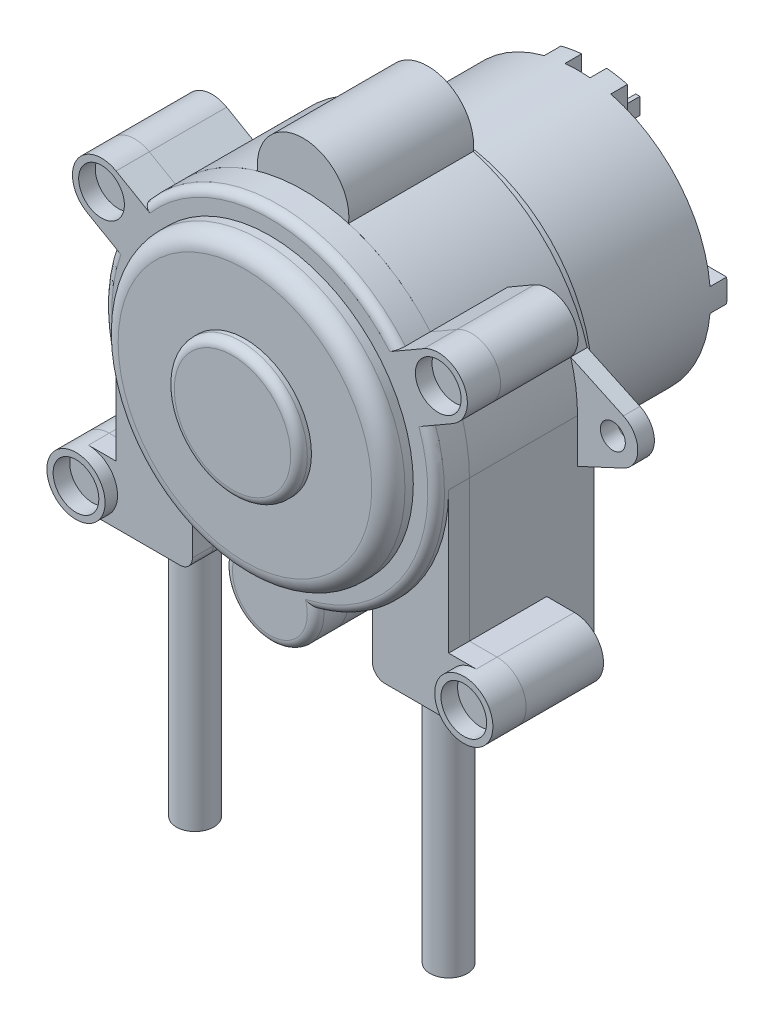
SolidWorks part; units mm, degrees
material "ABS"
ref_plane "Frontal" through (0, 0, 0) normal (0, 0, 1) x (1, 0, 0)
ref_plane "Superior" through (0, 0, 0) normal (0, 1, 0) x (1, 0, 0)
ref_plane "Direito" through (0, 0, 0) normal (1, 0, 0) x (0, 0, -1)
sketch "Esboço1" plane through (0, 0, 0) normal (0, 0, 1) x (1, 0, 0)
  line L0 (-20, 0) -> (20, 0) construction
  line L1 (-20, 0) -> (-20, -17)
  line L2 (-20, -17) -> (-23.325, -17)
  line L3 (-23.325, -24) -> (-12.325, -24)
  line L4 (-10.825, -22.5) -> (-10.825, -16.8172)
  line L5 (0, 20) -> (0, -20) construction
  line L6 (0, 0) -> (-20.25, 11.6913) construction
  line L7 (-18.5, 14.7224) -> (-15.3032, 12.8768)
  line L8 (-22, 8.6603) -> (-18.8032, 6.8146)
  line L9 (18.5, 14.7224) -> (15.3032, 12.8768)
  line L10 (22, 8.6603) -> (18.8032, 6.8146)
  line L11 (10.825, -22.5) -> (10.825, -16.8172)
  line L12 (23.325, -24) -> (12.325, -24)
  line L13 (20, -17) -> (23.325, -17)
  line L14 (20, 0) -> (20, -17)
  arc A0 (15.3032, 12.8768) -> (5.4603, 19.2402) centre (0, 0) ccw
  arc A1 (-23.325, -17) -> (-23.325, -24) centre (-23.325, -20.5) ccw
  arc A2 (-18.5, 14.7224) -> (-22, 8.6603) centre (-20.25, 11.6913) ccw
  arc A3 (18.5, 14.7224) -> (22, 8.6603) centre (20.25, 11.6913) cw
  arc A4 (-18.8032, 6.8146) -> (-20, 0) centre (0, 0) ccw
  arc A5 (-10.825, -16.8172) -> (-5.4603, -19.2402) centre (0, 0) ccw
  arc A6 (23.325, -17) -> (23.325, -24) centre (23.325, -20.5) cw
  arc A7 (20, 0) -> (18.8032, 6.8146) centre (0, 0) ccw
  arc A8 (5.4603, -19.2402) -> (-5.4603, -19.2402) centre (0, -19.9) cw
  arc A9 (5.4603, 19.2402) -> (-5.4603, 19.2402) centre (0, 19.9) ccw
  arc A10 (-5.4603, 19.2402) -> (-15.3032, 12.8768) centre (0, 0) ccw
  arc A11 (5.4603, -19.2402) -> (10.825, -16.8172) centre (0, 0) ccw
  arc A12 (10.825, -22.5) -> (12.325, -24) centre (12.325, -22.5) ccw
  arc A13 (-12.325, -24) -> (-10.825, -22.5) centre (-12.325, -22.5) ccw
  point P34 (0, -25.4)
  point P35 (0, 25.4)
  point P36 (26.825, -20.5)
  point P37 (-26.825, -20.5)
  point P40 (10.825, -24)
  point P43 (-10.825, -24)
  dimension "D1" = 40
  dimension "D4" = 47.5
  dimension "D7" = 7
  dimension "D6" = 5.5
  dimension "D8" = 53.65
  dimension "D11" = 1.5
  dimension "D2" = 60
  dimension "D3" = 7
  dimension "D5" = 50.8
  dimension "D9" = 44
  dimension "D10" = 16
extrude "Ressalto-extrusão1" add sketch "Esboço1" along normal blind 15
sketch "Esboço2" plane through (0, 0, 0) normal (0, 0, -1) x (-1, 0, 0)
  line L0 (-20, -17) -> (-20, -24)
  line L1 (20, -17) -> (20, -24)
  line L12 (-20, 0) -> (-20, -17)
  line L13 (-20, -17) -> (-23.325, -17)
  line L14 (-23.325, -24) -> (-12.325, -24)
  line L15 (-10.825, -22.5) -> (-10.825, -16.8172)
  line L16 (10.825, -16.8172) -> (10.825, -22.5)
  line L17 (12.325, -24) -> (23.325, -24)
  line L18 (23.325, -17) -> (20, -17)
  line L19 (20, -17) -> (20, 0)
  line L20 (18.8032, 6.8146) -> (22, 8.6603)
  line L21 (18.5, 14.7224) -> (15.3032, 12.8768)
  line L22 (-15.3032, 12.8768) -> (-18.5, 14.7224)
  line L23 (-22, 8.6603) -> (-18.8032, 6.8146)
  line L25 (-20, -17) -> (-23.325, -17)
  line L26 (-23.325, -24) -> (-20, -24)
  line L29 (20, -24) -> (23.325, -24)
  line L30 (23.325, -17) -> (20, -17)
  line L32 (18.8032, 6.8146) -> (22, 8.6603)
  line L33 (18.5, 14.7224) -> (15.3032, 12.8768)
  line L34 (-15.3032, 12.8768) -> (-18.5, 14.7224)
  line L35 (-22, 8.6603) -> (-18.8032, 6.8146)
  arc A1 (-15.3032, 12.8768) -> (-18.8032, 6.8146) centre (0, 0) ccw
  arc A3 (18.8032, 6.8146) -> (15.3032, 12.8768) centre (0, 0) ccw
  arc A13 (-18.8032, 6.8146) -> (-20, 0) centre (0, 0) ccw
  arc A14 (-23.325, -17) -> (-23.325, -24) centre (-23.325, -20.5) ccw
  arc A15 (-10.825, -16.8172) -> (-5.4603, -19.2402) centre (0, 0) ccw
  arc A16 (-5.4603, -19.2402) -> (5.4603, -19.2402) centre (0, -19.9) ccw
  arc A17 (5.4603, -19.2402) -> (10.825, -16.8172) centre (0, 0) ccw
  arc A18 (23.325, -24) -> (23.325, -17) centre (23.325, -20.5) ccw
  arc A19 (20, 0) -> (18.8032, 6.8146) centre (0, 0) ccw
  arc A20 (22, 8.6603) -> (18.5, 14.7224) centre (20.25, 11.6913) ccw
  arc A21 (15.3032, 12.8768) -> (5.4603, 19.2402) centre (0, 0) ccw
  arc A22 (5.4603, 19.2402) -> (-5.4603, 19.2402) centre (0, 19.9) ccw
  arc A23 (-5.4603, 19.2402) -> (-15.3032, 12.8768) centre (0, 0) ccw
  arc A24 (-18.5, 14.7224) -> (-22, 8.6603) centre (-20.25, 11.6913) ccw
  arc A26 (-23.325, -17) -> (-23.325, -24) centre (-23.325, -20.5) ccw
  arc A30 (23.325, -24) -> (23.325, -17) centre (23.325, -20.5) ccw
  arc A32 (22, 8.6603) -> (18.5, 14.7224) centre (20.25, 11.6913) ccw
  arc A36 (-18.5, 14.7224) -> (-22, 8.6603) centre (-20.25, 11.6913) ccw
  arc A42 (-12.325, -24) -> (-10.825, -22.5) centre (-12.325, -22.5) ccw
  arc A44 (10.825, -22.5) -> (12.325, -24) centre (12.325, -22.5) ccw
  dimension "D1" = 0
extrude "Corte-extrusão1" cut sketch "Esboço2" against normal blind 5.7
sketch "Esboço3" plane through (0, 0, 0) normal (0, 0, -1) x (-1, 0, 0)
  line L0 (-24.25, 0) -> (24.25, 0) construction
  line L1 (-25.5179, 2.7189) -> (0, 14.6181)
  line L2 (-25.5179, -2.7189) -> (0, -14.6181)
  line L3 (25.5179, 2.7189) -> (0, 14.6181)
  line L4 (25.5179, -2.7189) -> (0, -14.6181)
  circle A0 centre (-24.25, 0) radius 1.5
  circle A1 centre (24.25, 0) radius 1.5
  arc A2 (25.5179, 2.7189) -> (25.5179, -2.7189) centre (24.25, 0) cw
  arc A3 (-25.5179, 2.7189) -> (-25.5179, -2.7189) centre (-24.25, 0) ccw
  point P4 (0, 0)
  point P15 (27.25, 0)
  point P16 (-27.25, 0)
  dimension "D2" = 3
  dimension "D3" = 54.5
  dimension "D1" = 48.5
  dimension "D4" = 50
extrude "Ressalto-extrusão2" add sketch "Esboço3" against normal blind 2
sketch "Esboço4" plane through (0, 0, 15) normal (0, 0, 1) x (1, 0, 0)
  circle A0 centre (0, 0) radius 18
  arc A1 (15.3032, 12.8768) -> (5.4603, 19.2402) centre (0, 0) ccw construction
  dimension "D1" = 2
extrude "Corte-extrusão2" cut sketch "Esboço4" against normal blind 10
sketch "Esboço5" plane through (0, 0, 0) normal (0, 0, -1) x (-1, 0, 0)
  circle A0 centre (0, 0) radius 17.25
  dimension "D1" = 34.5
extrude "Ressalto-extrusão3" add sketch "Esboço5" along normal blind 2.5
sketch "Esboço6" plane through (0, 0, -2.5) normal (0, 0, -1) x (-1, 0, 0)
  circle A0 centre (0, 0) radius 16
  dimension "D1" = 32
extrude "Ressalto-extrusão4" add sketch "Esboço6" along normal blind 17.5 separate body
sketch "Esboço7" plane through (0, 0, -20) normal (0, 0, -1) x (-1, 0, 0)
  circle A0 centre (0, 0) radius 3.65
  dimension "D1" = 7.3
extrude "Ressalto-extrusão5" add sketch "Esboço7" along normal blind 3.5
sketch "Esboço8" plane through (0, 0, -20) normal (0, 0, -1) x (-1, 0, 0)
  line L0 (0, 16) -> (0, -16) construction
  line L1 (-16, 0) -> (16, 0) construction
  line L2 (-4, 15.4919) -> (-4, 3.4)
  line L3 (4, 15.4919) -> (4, 3.4)
  line L4 (-15.9386, -1.4) -> (-6, -1.4)
  line L5 (-15.9386, 1.4) -> (-6, 1.4)
  line L6 (-4, 16) -> (-4, -16) construction
  line L7 (4, 16) -> (4, -16) construction
  line L8 (4, -3.4) -> (4, -15.4919)
  line L9 (6, 1.4) -> (15.9386, 1.4)
  line L10 (-16, 1.4) -> (16, 1.4) construction
  line L11 (-4, -3.4) -> (-4, -15.4919)
  line L12 (6, -1.4) -> (15.9386, -1.4)
  line L13 (-16, -1.4) -> (16, -1.4) construction
  line L15 (-1.5, 19.15) -> (1.5, 19.15)
  line L16 (-1.5, 19.15) -> (-1.5, 12.85)
  line L17 (-1.5, 12.85) -> (1.5, 12.85)
  line L18 (1.5, 19.15) -> (1.5, 12.85)
  line L19 (-1.5, 19.15) -> (1.5, 12.85) construction
  line L20 (-1.5, 12.85) -> (1.5, 19.15) construction
  line L21 (-1.5, -12.85) -> (1.5, -12.85)
  line L22 (-1.5, -12.85) -> (-1.5, -19.15)
  line L23 (-1.5, -19.15) -> (1.5, -19.15)
  line L24 (1.5, -12.85) -> (1.5, -19.15)
  line L25 (-1.5, -12.85) -> (1.5, -19.15) construction
  line L26 (-1.5, -19.15) -> (1.5, -12.85) construction
  circle A0 centre (0, 0) radius 16 construction
  arc A1 (-4, 15.4919) -> (-15.9386, 1.4) centre (0, 0) ccw
  arc A2 (15.9386, 1.4) -> (4, 15.4919) centre (0, 0) ccw
  arc A3 (4, -15.4919) -> (15.9386, -1.4) centre (0, 0) ccw
  arc A4 (-15.9386, -1.4) -> (-4, -15.4919) centre (0, 0) ccw
  arc A5 (4, 3.4) -> (6, 1.4) centre (6, 3.4) ccw
  arc A6 (6, -1.4) -> (4, -3.4) centre (6, -3.4) ccw
  arc A7 (-4, -3.4) -> (-6, -1.4) centre (-6, -3.4) ccw
  arc A8 (-6, 1.4) -> (-4, 3.4) centre (-6, 3.4) ccw
  point P29 (4, 1.4)
  dimension "D5" = 2
  dimension "D6" = 3
  dimension "D7" = 25.7
  dimension "D1" = 4
  dimension "D2" = 4
  dimension "D3" = 1.4
  dimension "D4" = 1.4
extrude "Corte-extrusão3" cut sketch "Esboço8" against normal blind 2
sketch "Esboço9" plane through (0, 0, -20) normal (0, 0, -1) x (-1, 0, 0)
  line L0 (-4, 3.4) -> (-4, 15.4919) construction
  line L1 (-2, 11.5) -> (-1.5, 11.5)
  line L2 (-2, 11.5) -> (-2, 9.5)
  line L3 (-2, 9.5) -> (-1.5, 9.5)
  line L4 (-1.5, 11.5) -> (-1.5, 9.5)
  line L5 (-2, 11.5) -> (-1.5, 9.5) construction
  line L6 (-2, 9.5) -> (-1.5, 11.5) construction
  line L7 (1.5, -11.5) -> (2, -11.5)
  line L8 (1.5, -11.5) -> (1.5, -9.5)
  line L9 (1.5, -9.5) -> (2, -9.5)
  line L10 (2, -11.5) -> (2, -9.5)
  line L11 (1.5, -11.5) -> (2, -9.5) construction
  line L12 (1.5, -9.5) -> (2, -11.5) construction
  line L13 (4, -3.4) -> (4, -15.4919) construction
  point P0 (-1.75, 10.5)
  point P5 (1.75, -10.5)
  dimension "D1" = 2
  dimension "D2" = 0.5
  dimension "D3" = 2.5
  dimension "D4" = 11.5
  dimension "D5" = 11.5
  dimension "D6" = 2.5
extrude "Ressalto-extrusão6" add sketch "Esboço9" along normal blind 3.5
sketch "Esboço10" plane through (0, 0, 15) normal (0, 0, 1) x (1, 0, 0)
  line L12 (18.8032, 6.8146) -> (22, 8.6603)
  line L13 (18.5, 14.7224) -> (15.3032, 12.8768)
  line L14 (-15.3032, 12.8768) -> (-18.5, 14.7224)
  line L15 (-22, 8.6603) -> (-18.8032, 6.8146)
  line L16 (-20, 0) -> (-20, -17)
  line L17 (-20, -17) -> (-23.325, -17)
  line L18 (-23.325, -24) -> (-12.325, -24)
  line L19 (-10.825, -22.5) -> (-10.825, -16.8172)
  line L20 (10.825, -16.8172) -> (10.825, -22.5)
  line L21 (12.325, -24) -> (23.325, -24)
  line L22 (23.325, -17) -> (20, -17)
  line L23 (20, -17) -> (20, 0)
  line L24 (18.8032, 6.8146) -> (22, 8.6603)
  line L25 (18.5, 14.7224) -> (15.3032, 12.8768)
  line L26 (-15.3032, 12.8768) -> (-18.5, 14.7224)
  line L27 (-22, 8.6603) -> (-18.8032, 6.8146)
  line L28 (-20, 0) -> (-20, -17)
  line L29 (-20, -17) -> (-23.325, -17)
  line L30 (-23.325, -24) -> (-12.325, -24)
  line L31 (-10.825, -22.5) -> (-10.825, -16.8172)
  line L32 (10.825, -16.8172) -> (10.825, -22.5)
  line L33 (12.325, -24) -> (23.325, -24)
  line L34 (23.325, -17) -> (20, -17)
  line L35 (20, -17) -> (20, 0)
  arc A12 (20, 0) -> (18.8032, 6.8146) centre (0, 0) ccw
  arc A13 (22, 8.6603) -> (18.5, 14.7224) centre (20.25, 11.6913) ccw
  arc A14 (15.3032, 12.8768) -> (5.4603, 19.2402) centre (0, 0) ccw
  arc A15 (5.4603, 19.2402) -> (-5.4603, 19.2402) centre (0, 19.9) ccw
  arc A16 (-5.4603, 19.2402) -> (-15.3032, 12.8768) centre (0, 0) ccw
  arc A17 (-18.5, 14.7224) -> (-22, 8.6603) centre (-20.25, 11.6913) ccw
  arc A19 (-23.325, -17) -> (-23.325, -24) centre (-23.325, -20.5) ccw
  arc A20 (-10.825, -16.8172) -> (-5.4603, -19.2402) centre (0, 0) ccw
  arc A21 (-5.4603, -19.2402) -> (5.4603, -19.2402) centre (0, -19.9) ccw
  arc A22 (5.4603, -19.2402) -> (10.825, -16.8172) centre (0, 0) ccw
  arc A23 (23.325, -24) -> (23.325, -17) centre (23.325, -20.5) ccw
  arc A24 (20, 0) -> (18.8032, 6.8146) centre (0, 0) ccw
  arc A25 (22, 8.6603) -> (18.5, 14.7224) centre (20.25, 11.6913) ccw
  arc A28 (15.3032, 12.8768) -> (-15.3032, 12.8768) centre (0, 0) ccw
  arc A29 (-18.5, 14.7224) -> (-22, 8.6603) centre (-20.25, 11.6913) ccw
  arc A31 (-23.325, -17) -> (-23.325, -24) centre (-23.325, -20.5) ccw
  arc A32 (-10.825, -16.8172) -> (-5.4603, -19.2402) centre (0, 0) ccw
  arc A33 (-5.4603, -19.2402) -> (5.4603, -19.2402) centre (0, -19.9) ccw
  arc A34 (5.4603, -19.2402) -> (10.825, -16.8172) centre (0, 0) ccw
  arc A35 (23.325, -24) -> (23.325, -17) centre (23.325, -20.5) ccw
  arc A38 (-18.8032, 6.8146) -> (-20, 0) centre (0, 0) ccw
  arc A39 (-18.8032, 6.8146) -> (-20, 0) centre (0, 0) ccw
  arc A40 (-12.325, -24) -> (-10.825, -22.5) centre (-12.325, -22.5) ccw
  arc A41 (-12.325, -24) -> (-10.825, -22.5) centre (-12.325, -22.5) ccw
  arc A42 (10.825, -22.5) -> (12.325, -24) centre (12.325, -22.5) ccw
  arc A43 (10.825, -22.5) -> (12.325, -24) centre (12.325, -22.5) ccw
  dimension "D1" = 0
extrude "Ressalto-extrusão7" add sketch "Esboço10" along normal blind 2.5 separate body
sketch "Esboço11" plane through (0, 0, 17.5) normal (0, 0, 1) x (1, 0, 0)
  line L12 (18.5, 14.7224) -> (15.3032, 12.8768)
  line L13 (-15.3032, 12.8768) -> (-18.5, 14.7224)
  line L14 (-22, 8.6603) -> (-18.8032, 6.8146)
  line L15 (-20, 0) -> (-20, -17)
  line L16 (-20, -17) -> (-23.325, -17)
  line L17 (-23.325, -24) -> (-12.325, -24)
  line L18 (-10.825, -22.5) -> (-10.825, -16.8172)
  line L19 (10.825, -16.8172) -> (10.825, -22.5)
  line L20 (12.325, -24) -> (23.325, -24)
  line L21 (23.325, -17) -> (20, -17)
  line L22 (20, -17) -> (20, 0)
  line L23 (18.8032, 6.8146) -> (22, 8.6603)
  line L24 (18.5, 14.7224) -> (15.3032, 12.8768)
  line L25 (-15.3032, 12.8768) -> (-18.5, 14.7224)
  line L26 (-22, 8.6603) -> (-18.8032, 6.8146)
  line L35 (18.8032, 6.8146) -> (22, 8.6603)
  arc A0 (-23.325, -17) -> (-23.325, -24) centre (-23.325, -20.5) ccw construction
  circle A1 centre (-23.325, -20.5) radius 3.5
  arc A2 (23.325, -24) -> (23.325, -17) centre (23.325, -20.5) ccw construction
  circle A3 centre (23.325, -20.5) radius 3.5
  arc A12 (22, 8.6603) -> (18.5, 14.7224) centre (20.25, 11.6913) ccw
  arc A13 (15.3032, 12.8768) -> (-15.3032, 12.8768) centre (0, 0) ccw
  arc A14 (-18.5, 14.7224) -> (-22, 8.6603) centre (-20.25, 11.6913) ccw
  arc A15 (-18.8032, 6.8146) -> (-20, 0) centre (0, 0) ccw
  arc A16 (-23.325, -17) -> (-23.325, -24) centre (-23.325, -20.5) ccw
  arc A17 (-12.325, -24) -> (-10.825, -22.5) centre (-12.325, -22.5) ccw
  arc A18 (-10.825, -16.8172) -> (-5.4603, -19.2402) centre (0, 0) ccw
  arc A19 (-5.4603, -19.2402) -> (5.4603, -19.2402) centre (0, -19.9) ccw
  arc A20 (5.4603, -19.2402) -> (10.825, -16.8172) centre (0, 0) ccw
  arc A21 (10.825, -22.5) -> (12.325, -24) centre (12.325, -22.5) ccw
  arc A22 (23.325, -24) -> (23.325, -17) centre (23.325, -20.5) ccw
  arc A23 (20, 0) -> (18.8032, 6.8146) centre (0, 0) ccw
  arc A24 (22, 8.6603) -> (18.5, 14.7224) centre (20.25, 11.6913) ccw
  arc A25 (15.3032, 12.8768) -> (-15.3032, 12.8768) centre (0, 0) ccw
  arc A26 (-18.5, 14.7224) -> (-22, 8.6603) centre (-20.25, 11.6913) ccw
  arc A30 (-18.8032, 6.8146) -> (-5.4603, -19.2402) centre (0, 0) ccw
  arc A31 (-5.4603, -19.2402) -> (5.4603, -19.2402) centre (0, -19.9) ccw
  arc A35 (5.4603, -19.2402) -> (18.8032, 6.8146) centre (0, 0) ccw
  dimension "D1" = 0
extrude "Ressalto-extrusão8" add sketch "Esboço11" along normal blind 1.5
sketch "Esboço12" plane through (0, 0, 19) normal (0, 0, 1) x (1, 0, 0)
  circle A0 centre (0, 0) radius 17.25
  dimension "D1" = 34.5
extrude "Ressalto-extrusão9" add sketch "Esboço12" along normal blind 3
sketch "Esboço13" plane through (0, 0, 22) normal (0, 0, 1) x (1, 0, 0)
  circle A0 centre (0, 0) radius 8
  dimension "D1" = 16
extrude "Ressalto-extrusão10" add sketch "Esboço13" along normal blind 1.5
sketch "Esboço14" plane through (0, 0, 19) normal (0, 0, 1) x (1, 0, 0)
  circle A0 centre (-23.325, -20.5) radius 2.75
  circle A1 centre (23.325, -20.5) radius 2.75
  circle A2 centre (20.25, 11.6913) radius 2.75
  circle A3 centre (-20.25, 11.6913) radius 2.75
  dimension "D1" = 5.5
extrude "Corte-extrusão4" cut sketch "Esboço14" against normal blind 2
sketch "Esboço15" plane through (0, -24, 0) normal (0, -1, 0) x (1, 0, 0)
  line L0 (12.325, 15) -> (23.325, 15) construction
  line L1 (-23.325, 15) -> (-12.325, 15) construction
  line L2 (-15.25, 12.75) -> (15.25, 12.75) construction
  circle A0 centre (-15.25, 12.75) radius 2.25
  circle A1 centre (15.25, 12.75) radius 2.25
  point P8 (0, 12.75)
  dimension "D1" = 30.5
  dimension "D2" = 4.5
extrude "Ressalto-extrusão11" add sketch "Esboço15" along normal blind 30 separate body
fillet "Filete1" radius 2 1 edges at (17.25, 0, 22)
fillet "Filete2" radius 1 5 edges at (0, 20, 19) (17.8015, -9.1163, 19) (0, -25.4, 19) (-17.8015, -9.1163, 19) (8, 0, 23.5)
sketch "Esboço16" plane through (0, 0, 5) normal (0, 0, 1) x (1, 0, 0)
  line L0 (0, 0) -> (0, 10.5) construction
  circle A0 centre (0, 10.5) radius 6.75
  circle A1 centre (9.0933, -5.25) radius 6.75
  circle A2 centre (-9.0933, -5.25) radius 6.75
  point P11 (0, 0)
  dimension "D1" = 13.5
  dimension "D2" = 10.5
  dimension "D3" = 3
extrude "Ressalto-extrusão12" add sketch "Esboço16" along normal blind 10 separate body
sketch "Esboço17" plane through (0, 0, 15) normal (0, 0, 1) x (1, 0, 0)
  line L0 (5, 10.5) -> (5, 5.7735)
  line L1 (11.5933, -0.9199) -> (7.5, 1.4434)
  line L2 (0, 0) -> (9.0933, -5.25) construction
  line L3 (0, 0) -> (0, 10.5) construction
  line L4 (-5, 10.5) -> (-5, 5.7735)
  line L5 (-11.5933, -0.9199) -> (-7.5, 1.4434)
  line L6 (-6.5933, -9.5801) -> (-2.5, -7.2169)
  line L7 (2.5, -7.2169) -> (6.5933, -9.5801)
  arc A0 (5, 10.5) -> (-5, 10.5) centre (0, 10.5) ccw
  arc A1 (-11.5933, -0.9199) -> (-6.5933, -9.5801) centre (-9.0933, -5.25) ccw
  arc A2 (6.5933, -9.5801) -> (11.5933, -0.9199) centre (9.0933, -5.25) ccw
  arc A3 (5, 5.7735) -> (7.5, 1.4434) centre (10, 5.7735) ccw
  arc A4 (-5, 5.7735) -> (-7.5, 1.4434) centre (-10, 5.7735) cw
  arc A5 (-2.5, -7.2169) -> (2.5, -7.2169) centre (0, -11.547) cw
  dimension "D2" = 5
  dimension "D3" = 5
extrude "Ressalto-extrusão13" add sketch "Esboço17" along normal blind 1 separate body
